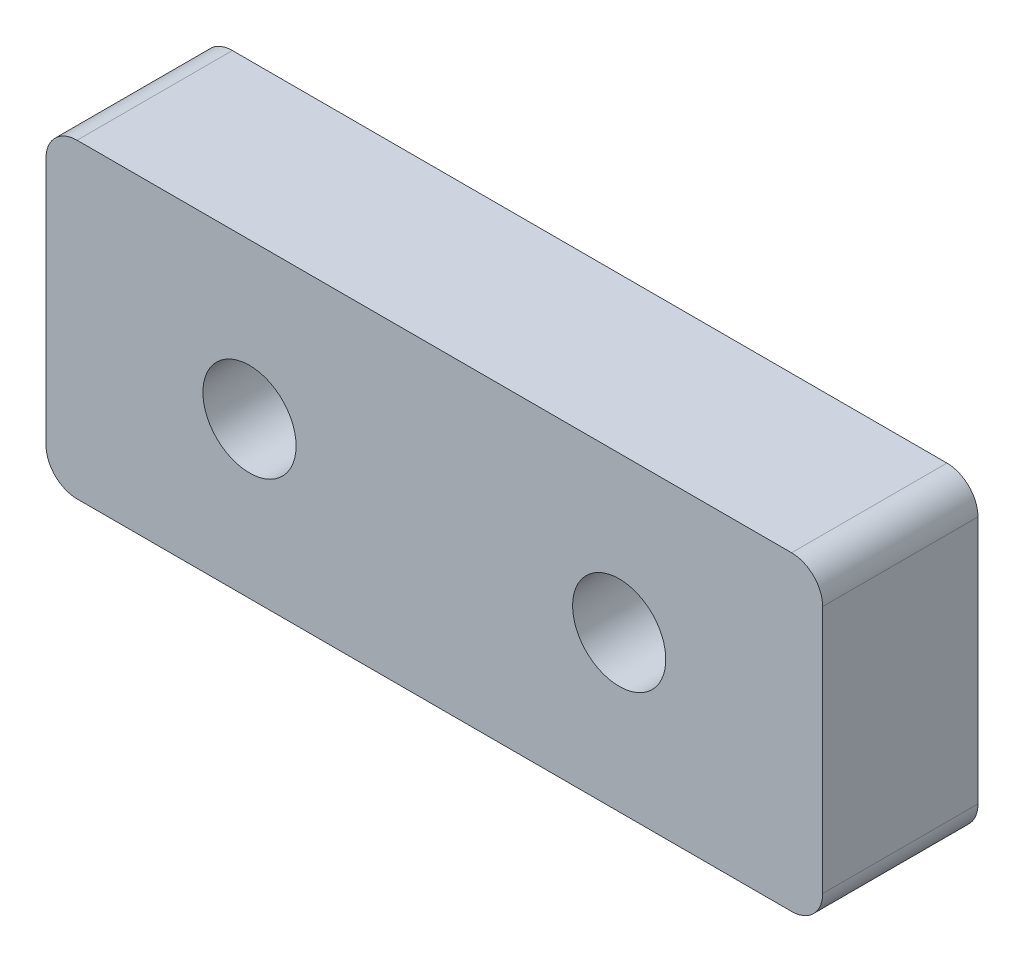
SolidWorks part; units mm, degrees
ref_plane "前视基准面" through (0, 0, 0) normal (0, 0, 1) x (1, 0, 0)
ref_plane "上视基准面" through (0, 0, 0) normal (0, 1, 0) x (1, 0, 0)
ref_plane "右视基准面" through (0, 0, 0) normal (1, 0, 0) x (0, 0, -1)
sketch "草图1" plane through (0, 0, 0) normal (0, 0, 1) x (1, 0, 0)
  line L0 (0, 5) -> (0, -9.3792) construction
  line L1 (-12.5, -5) -> (12.5, -5)
  line L2 (-12.5, -5) -> (-12.5, 5)
  line L3 (-12.5, 5) -> (12.5, 5)
  line L4 (12.5, -5) -> (12.5, 5)
  line L5 (-12.5, -5) -> (12.5, 5) construction
  line L6 (-12.5, 5) -> (12.5, -5) construction
  circle A0 centre (-5.95, 0) radius 1.5
  circle A1 centre (5.95, 0) radius 1.5
  point P0 (0, 0)
  dimension "D3" = 3
  dimension "D5" = 5
  dimension "D1" = 25
  dimension "D2" = 10
  dimension "D4" = 11.9
extrude "凸台-拉伸1" add sketch "草图1" along normal blind 5
fillet "圆角1" radius 1 4 edges at (12.5, 5, 2.5) (12.5, -5, 2.5) (-12.5, -5, 2.5) (-12.5, 5, 2.5)
